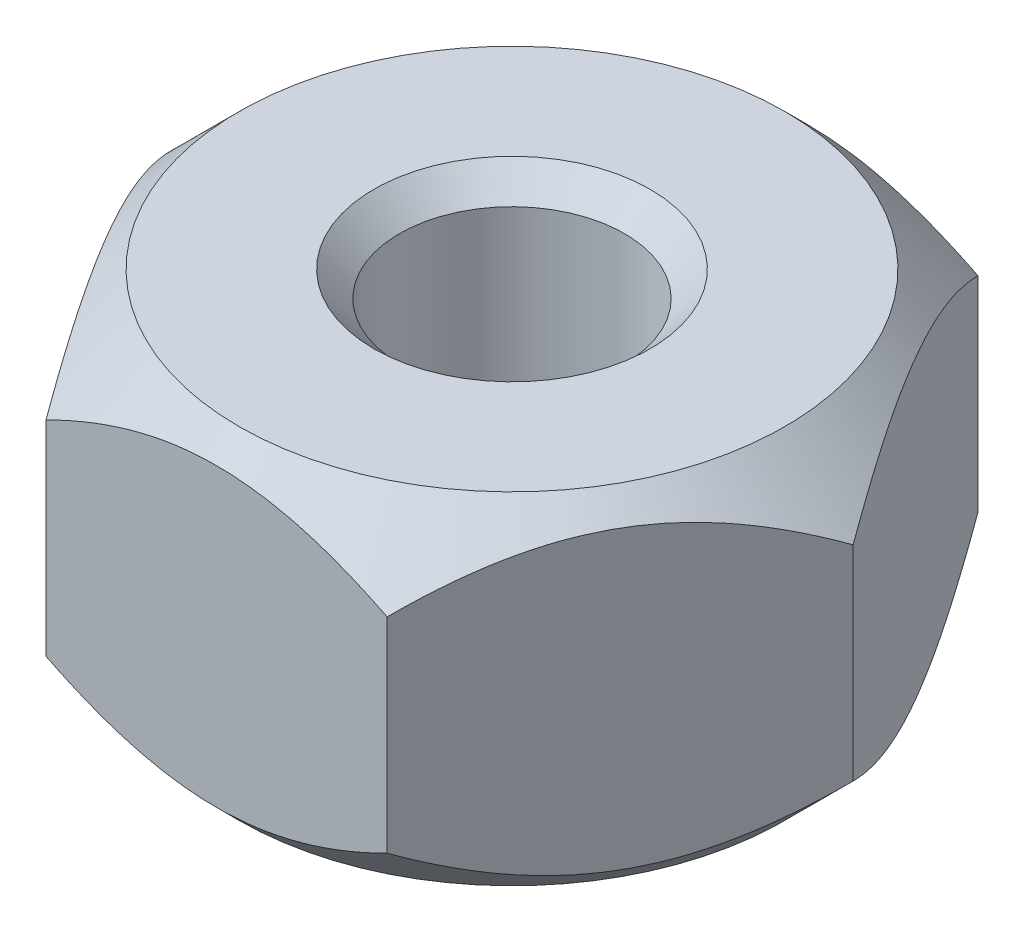
SolidWorks part; units mm, degrees
ref_plane "Front Plane" through (0, 0, 0) normal (0, 0, 1) x (1, 0, 0)
ref_plane "Top Plane" through (0, 0, 0) normal (0, 1, 0) x (1, 0, 0)
ref_plane "Right Plane" through (0, 0, 0) normal (1, 0, 0) x (0, 0, -1)
sketch "Sketch1" plane through (0, 0, 0) normal (0, 1, 0) x (1, 0, 0)
  line L1 (2.5, -4.3301) -> (5, 0)
  line L2 (5, 0) -> (2.5, 4.3301)
  line L3 (2.5, 4.3301) -> (-2.5, 4.3301)
  line L4 (-2.5, 4.3301) -> (-5, 0)
  line L5 (-5, 0) -> (-2.5, -4.3301)
  line L6 (-2.5, -4.3301) -> (2.5, -4.3301)
  circle A0 centre (0, 0) radius 4.3301 construction
  dimension "D1" = 10
extrude "Boss-Extrude1" add sketch "Sketch1" along normal mid plane 5
sketch "Sketch2" plane through (0, 0, 0) normal (0, 0, 1) x (1, 0, 0)
  line L0 (4, 2.5) -> (5, 1.5)
  line L1 (2.5, 2.5) -> (5, 2.5) construction
  line L2 (5, 2.5) -> (5, -2.5) construction
  line L3 (4, 2.5) -> (5, 2.5)
  line L4 (5, 2.5) -> (5, 1.5)
  line L5 (0, 0) -> (0, 3.6808) construction
  dimension "D1" = 1
  dimension "D2" = 1
revolve "Cut-Revolve1" cut sketch "Sketch2" angle 360 about L5
mirror "Mirror1" about plane through (0, 0, 0) normal (0, 1, 0) of "Cut-Revolve1"
hole_wizard "M4x0.7 Tapped Hole1" positions "Sketch3" profile "Sketch4" tap size "M4x0.7" standard "ANSI Metric"
sketch "Sketch3" plane through (0, 2.5, 0) normal (0, 1, 0) x (1, 0, 0)
  point P0 (0, 0)
  point P4 (0, 0)
sketch "Sketch4" plane through (0, 2.5, 0) normal (1, 0, 0) x (0, 0, 1)
  line L0 (0, 0) -> (0, 10.1)
  line L1 (0, 10.1) -> (1.65, 9.1086)
  line L2 (1.65, 9.1086) -> (1.65, 0.375)
  line L3 (1.65, 0.375) -> (2.025, 0)
  line L5 (2.025, 0) -> (0, 0)
  line L6 (-1.65, 0.375) -> (-2.025, 0) construction
  line L10 (0, 10.1) -> (-1.65, 9.1086) construction
  line L11 (0, -6.35) -> (0, 107.95) construction
  dimension "Tap Drill Dia." = 3.3
  dimension "Tap Drill Depth" = 10.1
  dimension "Near C'Sink Dia." = 4.05
  dimension "Near C'Sink Angle" = 90
  dimension "Drill Angle" = 118
cosmetic thread "Hole Thread1" parameters "D1"=8, "D2"=4
